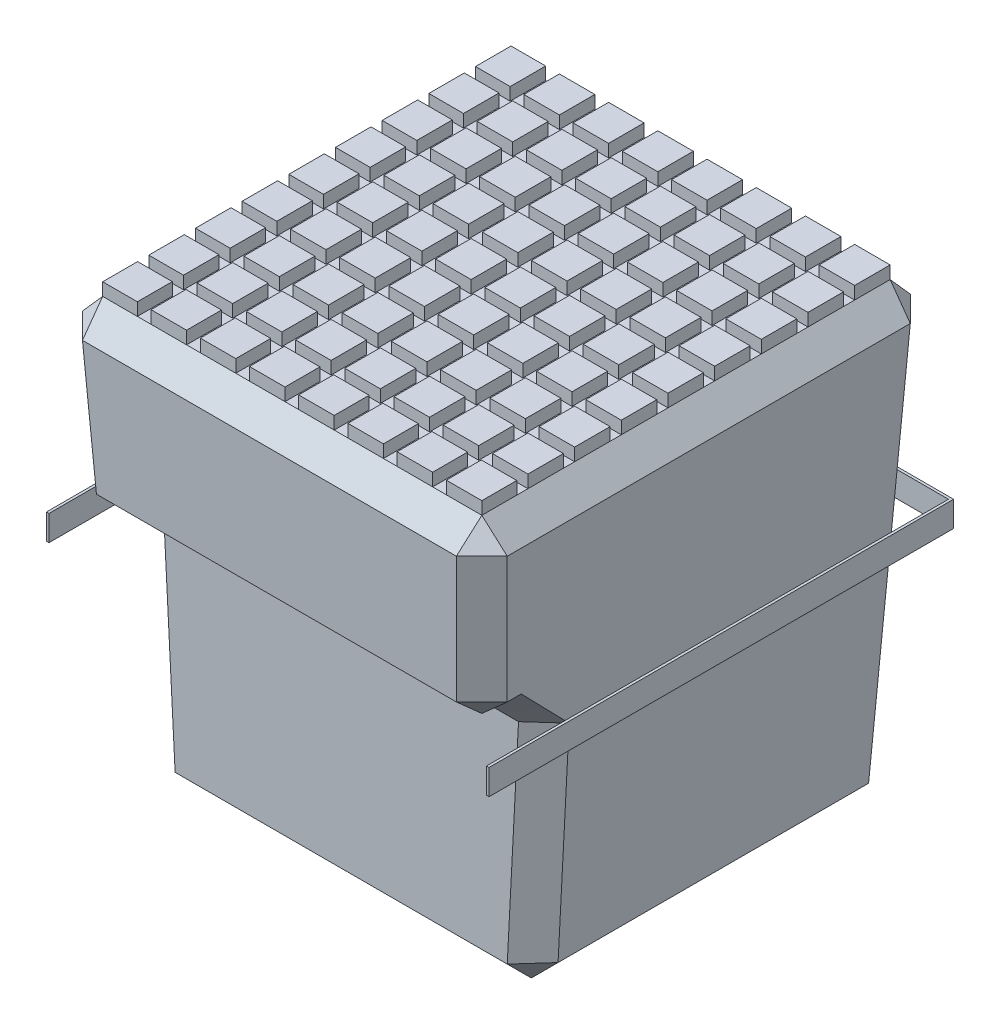
SolidWorks part; units mm, degrees
material "Stainless Steel 2205"
ref_plane "Front Plane" through (0, 0, 0) normal (0, 0, 1) x (1, 0, 0)
ref_plane "Top Plane" through (0, 0, 0) normal (0, 1, 0) x (1, 0, 0)
ref_plane "Right Plane" through (0, 0, 0) normal (1, 0, 0) x (0, 0, -1)
sketch "Sketch2" plane through (0, 0, 0) normal (0, 1, 0) x (1, 0, 0)
  line L1 (168.5, 180) -> (-168.5, 180)
  line L2 (168.5, 180) -> (168.5, -180)
  line L3 (168.5, -180) -> (-168.5, -180)
  line L4 (-168.5, 180) -> (-168.5, -180)
  line L5 (168.5, 180) -> (-168.5, -180) construction
  line L6 (168.5, -180) -> (-168.5, 180) construction
  point P0 (0, 0)
  dimension "D1" = 337
  dimension "D2" = 360
extrude "Boss-Extrude1" add sketch "Sketch2" against normal blind 355 draft 3
sketch "Sketch4" plane through (0, 0, 0) normal (1, 0, 0) x (0, 0, -1)
  line L0 (-172.4009, -145) -> (-122.4009, -145)
  line L1 (-161.3952, -355) -> (-180, 0) construction
  line L2 (-122.4009, -145) -> (-122.4009, -355)
  line L3 (-161.3952, -355) -> (161.3952, -355) construction
  line L4 (-122.4009, -355) -> (-170.6976, -355)
  line L5 (-170.6976, -355) -> (-172.4009, -145)
  dimension "D1" = 50
  dimension "D2" = 210
extrude "Cut-Extrude1" cut sketch "Sketch4" against normal through all and the other way through all
chamfer "Chamfer1" distance 20 angle 45 18 edges at (-159.1976, -177.5, -170.6976) (159.1976, -177.5, -170.6976) (-164.7004, -72.5, 176.2004) (0, 0, -180) (-168.5, 0, 0) (168.5, 0, 0) (0, 0, 180) (164.7004, -72.5, 176.2004) (-160.9009, -145, 147.4009) (160.9009, -145, 147.4009) (0, -145, 172.4009) (149.8952, -355, -19.4972) (0, -355, -161.3952) (-149.8952, -355, -19.4972) (0, -145, 122.4009) (155.3981, -250, 122.4009) (0, -355, 122.4009) (-155.3981, -250, 122.4009)
sketch "Sketch5" plane through (0, 0, 0) normal (0, 1, 0) x (1, 0, 0)
  line L0 (0, 122.6349) -> (0, -123.659)
  line L1 (149.4699, 124.1699) -> (149.4699, 96.1699)
  line L2 (149.4699, 160.9699) -> (121.4699, 160.9699)
  line L3 (149.4699, 160.9699) -> (149.4699, 132.9699)
  line L4 (149.4699, 132.9699) -> (121.4699, 132.9699)
  line L5 (121.4699, 160.9699) -> (121.4699, 132.9699)
  line L6 (149.4699, 124.1699) -> (121.4699, 124.1699)
  line L7 (121.4699, 124.1699) -> (121.4699, 96.1699)
  line L8 (149.4699, 96.1699) -> (121.4699, 96.1699)
  line L9 (149.4699, 87.3699) -> (149.4699, 59.3699)
  line L10 (149.4699, 87.3699) -> (121.4699, 87.3699)
  line L11 (121.4699, 87.3699) -> (121.4699, 59.3699)
  line L12 (149.4699, 59.3699) -> (121.4699, 59.3699)
  line L13 (149.4699, 50.5699) -> (149.4699, 22.5699)
  line L14 (149.4699, 50.5699) -> (121.4699, 50.5699)
  line L15 (121.4699, 50.5699) -> (121.4699, 22.5699)
  line L16 (149.4699, 22.5699) -> (121.4699, 22.5699)
  line L17 (149.4699, 13.7699) -> (149.4699, -14.2301)
  line L18 (149.4699, 13.7699) -> (121.4699, 13.7699)
  line L19 (121.4699, 13.7699) -> (121.4699, -14.2301)
  line L20 (149.4699, -14.2301) -> (121.4699, -14.2301)
  line L21 (149.4699, -23.0301) -> (149.4699, -51.0301)
  line L22 (149.4699, -23.0301) -> (121.4699, -23.0301)
  line L23 (121.4699, -23.0301) -> (121.4699, -51.0301)
  line L24 (149.4699, -51.0301) -> (121.4699, -51.0301)
  line L25 (149.4699, -59.8301) -> (149.4699, -87.8301)
  line L26 (149.4699, -59.8301) -> (121.4699, -59.8301)
  line L27 (121.4699, -59.8301) -> (121.4699, -87.8301)
  line L28 (149.4699, -87.8301) -> (121.4699, -87.8301)
  line L29 (149.4699, -96.6301) -> (149.4699, -124.6301)
  line L30 (149.4699, -96.6301) -> (121.4699, -96.6301)
  line L31 (121.4699, -96.6301) -> (121.4699, -124.6301)
  line L32 (149.4699, -124.6301) -> (121.4699, -124.6301)
  line L33 (149.4699, -133.4301) -> (149.4699, -161.4301)
  line L34 (149.4699, -133.4301) -> (121.4699, -133.4301)
  line L35 (121.4699, -133.4301) -> (121.4699, -161.4301)
  line L36 (149.4699, -161.4301) -> (121.4699, -161.4301)
  line L37 (149.4699, 160.9699) -> (149.4699, 124.1699) construction
  line L38 (110.6699, 160.9699) -> (110.6699, 132.9699)
  line L39 (110.6699, 160.9699) -> (82.6699, 160.9699)
  line L40 (82.6699, 160.9699) -> (82.6699, 132.9699)
  line L41 (110.6699, 132.9699) -> (82.6699, 132.9699)
  line L42 (71.8699, 160.9699) -> (71.8699, 132.9699)
  line L43 (71.8699, 160.9699) -> (43.8699, 160.9699)
  line L44 (43.8699, 160.9699) -> (43.8699, 132.9699)
  line L45 (71.8699, 132.9699) -> (43.8699, 132.9699)
  line L46 (33.0699, 160.9699) -> (33.0699, 132.9699)
  line L47 (33.0699, 160.9699) -> (5.0699, 160.9699)
  line L48 (5.0699, 160.9699) -> (5.0699, 132.9699)
  line L49 (33.0699, 132.9699) -> (5.0699, 132.9699)
  line L50 (-5.7301, 160.9699) -> (-5.7301, 132.9699)
  line L51 (-5.7301, 160.9699) -> (-33.7301, 160.9699)
  line L52 (-33.7301, 160.9699) -> (-33.7301, 132.9699)
  line L53 (-5.7301, 132.9699) -> (-33.7301, 132.9699)
  line L54 (-44.5301, 160.9699) -> (-44.5301, 132.9699)
  line L55 (-44.5301, 160.9699) -> (-72.5301, 160.9699)
  line L56 (-72.5301, 160.9699) -> (-72.5301, 132.9699)
  line L57 (-44.5301, 132.9699) -> (-72.5301, 132.9699)
  line L58 (-83.3301, 160.9699) -> (-83.3301, 132.9699)
  line L59 (-83.3301, 160.9699) -> (-111.3301, 160.9699)
  line L60 (-111.3301, 160.9699) -> (-111.3301, 132.9699)
  line L61 (-83.3301, 132.9699) -> (-111.3301, 132.9699)
  line L62 (-122.1301, 160.9699) -> (-122.1301, 132.9699)
  line L63 (-122.1301, 160.9699) -> (-150.1301, 160.9699)
  line L64 (-150.1301, 160.9699) -> (-150.1301, 132.9699)
  line L65 (-122.1301, 132.9699) -> (-150.1301, 132.9699)
  line L66 (110.6699, 124.1699) -> (110.6699, 96.1699)
  line L67 (110.6699, 124.1699) -> (82.6699, 124.1699)
  line L68 (82.6699, 124.1699) -> (82.6699, 96.1699)
  line L69 (110.6699, 96.1699) -> (82.6699, 96.1699)
  line L70 (71.8699, 124.1699) -> (71.8699, 96.1699)
  line L71 (71.8699, 124.1699) -> (43.8699, 124.1699)
  line L72 (43.8699, 124.1699) -> (43.8699, 96.1699)
  line L73 (71.8699, 96.1699) -> (43.8699, 96.1699)
  line L74 (33.0699, 124.1699) -> (33.0699, 96.1699)
  line L75 (33.0699, 124.1699) -> (5.0699, 124.1699)
  line L76 (5.0699, 124.1699) -> (5.0699, 96.1699)
  line L77 (33.0699, 96.1699) -> (5.0699, 96.1699)
  line L78 (-5.7301, 124.1699) -> (-5.7301, 96.1699)
  line L79 (-5.7301, 124.1699) -> (-33.7301, 124.1699)
  line L80 (-33.7301, 124.1699) -> (-33.7301, 96.1699)
  line L81 (-5.7301, 96.1699) -> (-33.7301, 96.1699)
  line L82 (-44.5301, 124.1699) -> (-44.5301, 96.1699)
  line L83 (-44.5301, 124.1699) -> (-72.5301, 124.1699)
  line L84 (-72.5301, 124.1699) -> (-72.5301, 96.1699)
  line L85 (-44.5301, 96.1699) -> (-72.5301, 96.1699)
  line L86 (-83.3301, 124.1699) -> (-83.3301, 96.1699)
  line L87 (-83.3301, 124.1699) -> (-111.3301, 124.1699)
  line L88 (-111.3301, 124.1699) -> (-111.3301, 96.1699)
  line L89 (-83.3301, 96.1699) -> (-111.3301, 96.1699)
  line L90 (-122.1301, 124.1699) -> (-122.1301, 96.1699)
  line L91 (-122.1301, 124.1699) -> (-150.1301, 124.1699)
  line L92 (-150.1301, 124.1699) -> (-150.1301, 96.1699)
  line L93 (-122.1301, 96.1699) -> (-150.1301, 96.1699)
  line L94 (110.6699, 87.3699) -> (110.6699, 59.3699)
  line L95 (110.6699, 87.3699) -> (82.6699, 87.3699)
  line L96 (82.6699, 87.3699) -> (82.6699, 59.3699)
  line L97 (110.6699, 59.3699) -> (82.6699, 59.3699)
  line L98 (71.8699, 87.3699) -> (71.8699, 59.3699)
  line L99 (71.8699, 87.3699) -> (43.8699, 87.3699)
  line L100 (43.8699, 87.3699) -> (43.8699, 59.3699)
  line L101 (71.8699, 59.3699) -> (43.8699, 59.3699)
  line L102 (33.0699, 87.3699) -> (33.0699, 59.3699)
  line L103 (33.0699, 87.3699) -> (5.0699, 87.3699)
  line L104 (5.0699, 87.3699) -> (5.0699, 59.3699)
  line L105 (33.0699, 59.3699) -> (5.0699, 59.3699)
  line L106 (-5.7301, 87.3699) -> (-5.7301, 59.3699)
  line L107 (-5.7301, 87.3699) -> (-33.7301, 87.3699)
  line L108 (-33.7301, 87.3699) -> (-33.7301, 59.3699)
  line L109 (-5.7301, 59.3699) -> (-33.7301, 59.3699)
  line L110 (-44.5301, 87.3699) -> (-44.5301, 59.3699)
  line L111 (-44.5301, 87.3699) -> (-72.5301, 87.3699)
  line L112 (-72.5301, 87.3699) -> (-72.5301, 59.3699)
  line L113 (-44.5301, 59.3699) -> (-72.5301, 59.3699)
  line L114 (-83.3301, 87.3699) -> (-83.3301, 59.3699)
  line L115 (-83.3301, 87.3699) -> (-111.3301, 87.3699)
  line L116 (-111.3301, 87.3699) -> (-111.3301, 59.3699)
  line L117 (-83.3301, 59.3699) -> (-111.3301, 59.3699)
  line L118 (-122.1301, 87.3699) -> (-122.1301, 59.3699)
  line L119 (-122.1301, 87.3699) -> (-150.1301, 87.3699)
  line L120 (-150.1301, 87.3699) -> (-150.1301, 59.3699)
  line L121 (-122.1301, 59.3699) -> (-150.1301, 59.3699)
  line L122 (110.6699, 50.5699) -> (110.6699, 22.5699)
  line L123 (110.6699, 50.5699) -> (82.6699, 50.5699)
  line L124 (82.6699, 50.5699) -> (82.6699, 22.5699)
  line L125 (110.6699, 22.5699) -> (82.6699, 22.5699)
  line L126 (71.8699, 50.5699) -> (71.8699, 22.5699)
  line L127 (71.8699, 50.5699) -> (43.8699, 50.5699)
  line L128 (43.8699, 50.5699) -> (43.8699, 22.5699)
  line L129 (71.8699, 22.5699) -> (43.8699, 22.5699)
  line L130 (33.0699, 50.5699) -> (33.0699, 22.5699)
  line L131 (33.0699, 50.5699) -> (5.0699, 50.5699)
  line L132 (5.0699, 50.5699) -> (5.0699, 22.5699)
  line L133 (33.0699, 22.5699) -> (5.0699, 22.5699)
  line L134 (-5.7301, 50.5699) -> (-5.7301, 22.5699)
  line L135 (-5.7301, 50.5699) -> (-33.7301, 50.5699)
  line L136 (-33.7301, 50.5699) -> (-33.7301, 22.5699)
  line L137 (-5.7301, 22.5699) -> (-33.7301, 22.5699)
  line L138 (-44.5301, 50.5699) -> (-44.5301, 22.5699)
  line L139 (-44.5301, 50.5699) -> (-72.5301, 50.5699)
  line L140 (-72.5301, 50.5699) -> (-72.5301, 22.5699)
  line L141 (-44.5301, 22.5699) -> (-72.5301, 22.5699)
  line L142 (-83.3301, 50.5699) -> (-83.3301, 22.5699)
  line L143 (-83.3301, 50.5699) -> (-111.3301, 50.5699)
  line L144 (-111.3301, 50.5699) -> (-111.3301, 22.5699)
  line L145 (-83.3301, 22.5699) -> (-111.3301, 22.5699)
  line L146 (-122.1301, 50.5699) -> (-122.1301, 22.5699)
  line L147 (-122.1301, 50.5699) -> (-150.1301, 50.5699)
  line L148 (-150.1301, 50.5699) -> (-150.1301, 22.5699)
  line L149 (-122.1301, 22.5699) -> (-150.1301, 22.5699)
  line L150 (110.6699, 13.7699) -> (110.6699, -14.2301)
  line L151 (110.6699, 13.7699) -> (82.6699, 13.7699)
  line L152 (82.6699, 13.7699) -> (82.6699, -14.2301)
  line L153 (110.6699, -14.2301) -> (82.6699, -14.2301)
  line L154 (71.8699, 13.7699) -> (71.8699, -14.2301)
  line L155 (71.8699, 13.7699) -> (43.8699, 13.7699)
  line L156 (43.8699, 13.7699) -> (43.8699, -14.2301)
  line L157 (71.8699, -14.2301) -> (43.8699, -14.2301)
  line L158 (33.0699, 13.7699) -> (33.0699, -14.2301)
  line L159 (33.0699, 13.7699) -> (5.0699, 13.7699)
  line L160 (5.0699, 13.7699) -> (5.0699, -14.2301)
  line L161 (33.0699, -14.2301) -> (5.0699, -14.2301)
  line L162 (-5.7301, 13.7699) -> (-5.7301, -14.2301)
  line L163 (-5.7301, 13.7699) -> (-33.7301, 13.7699)
  line L164 (-33.7301, 13.7699) -> (-33.7301, -14.2301)
  line L165 (-5.7301, -14.2301) -> (-33.7301, -14.2301)
  line L166 (-44.5301, 13.7699) -> (-44.5301, -14.2301)
  line L167 (-44.5301, 13.7699) -> (-72.5301, 13.7699)
  line L168 (-72.5301, 13.7699) -> (-72.5301, -14.2301)
  line L169 (-44.5301, -14.2301) -> (-72.5301, -14.2301)
  line L170 (-83.3301, 13.7699) -> (-83.3301, -14.2301)
  line L171 (-83.3301, 13.7699) -> (-111.3301, 13.7699)
  line L172 (-111.3301, 13.7699) -> (-111.3301, -14.2301)
  line L173 (-83.3301, -14.2301) -> (-111.3301, -14.2301)
  line L174 (-122.1301, 13.7699) -> (-122.1301, -14.2301)
  line L175 (-122.1301, 13.7699) -> (-150.1301, 13.7699)
  line L176 (-150.1301, 13.7699) -> (-150.1301, -14.2301)
  line L177 (-122.1301, -14.2301) -> (-150.1301, -14.2301)
  line L178 (110.6699, -23.0301) -> (110.6699, -51.0301)
  line L179 (110.6699, -23.0301) -> (82.6699, -23.0301)
  line L180 (82.6699, -23.0301) -> (82.6699, -51.0301)
  line L181 (110.6699, -51.0301) -> (82.6699, -51.0301)
  line L182 (71.8699, -23.0301) -> (71.8699, -51.0301)
  line L183 (71.8699, -23.0301) -> (43.8699, -23.0301)
  line L184 (43.8699, -23.0301) -> (43.8699, -51.0301)
  line L185 (71.8699, -51.0301) -> (43.8699, -51.0301)
  line L186 (33.0699, -23.0301) -> (33.0699, -51.0301)
  line L187 (33.0699, -23.0301) -> (5.0699, -23.0301)
  line L188 (5.0699, -23.0301) -> (5.0699, -51.0301)
  line L189 (33.0699, -51.0301) -> (5.0699, -51.0301)
  line L190 (-5.7301, -23.0301) -> (-5.7301, -51.0301)
  line L191 (-5.7301, -23.0301) -> (-33.7301, -23.0301)
  line L192 (-33.7301, -23.0301) -> (-33.7301, -51.0301)
  line L193 (-5.7301, -51.0301) -> (-33.7301, -51.0301)
  line L194 (-44.5301, -23.0301) -> (-44.5301, -51.0301)
  line L195 (-44.5301, -23.0301) -> (-72.5301, -23.0301)
  line L196 (-72.5301, -23.0301) -> (-72.5301, -51.0301)
  line L197 (-44.5301, -51.0301) -> (-72.5301, -51.0301)
  line L198 (-83.3301, -23.0301) -> (-83.3301, -51.0301)
  line L199 (-83.3301, -23.0301) -> (-111.3301, -23.0301)
  line L200 (-111.3301, -23.0301) -> (-111.3301, -51.0301)
  line L201 (-83.3301, -51.0301) -> (-111.3301, -51.0301)
  line L202 (-122.1301, -23.0301) -> (-122.1301, -51.0301)
  line L203 (-122.1301, -23.0301) -> (-150.1301, -23.0301)
  line L204 (-150.1301, -23.0301) -> (-150.1301, -51.0301)
  line L205 (-122.1301, -51.0301) -> (-150.1301, -51.0301)
  line L206 (110.6699, -59.8301) -> (110.6699, -87.8301)
  line L207 (110.6699, -59.8301) -> (82.6699, -59.8301)
  line L208 (82.6699, -59.8301) -> (82.6699, -87.8301)
  line L209 (110.6699, -87.8301) -> (82.6699, -87.8301)
  line L210 (71.8699, -59.8301) -> (71.8699, -87.8301)
  line L211 (71.8699, -59.8301) -> (43.8699, -59.8301)
  line L212 (43.8699, -59.8301) -> (43.8699, -87.8301)
  line L213 (71.8699, -87.8301) -> (43.8699, -87.8301)
  line L214 (33.0699, -59.8301) -> (33.0699, -87.8301)
  line L215 (33.0699, -59.8301) -> (5.0699, -59.8301)
  line L216 (5.0699, -59.8301) -> (5.0699, -87.8301)
  line L217 (33.0699, -87.8301) -> (5.0699, -87.8301)
  line L218 (-5.7301, -59.8301) -> (-5.7301, -87.8301)
  line L219 (-5.7301, -59.8301) -> (-33.7301, -59.8301)
  line L220 (-33.7301, -59.8301) -> (-33.7301, -87.8301)
  line L221 (-5.7301, -87.8301) -> (-33.7301, -87.8301)
  line L222 (-44.5301, -59.8301) -> (-44.5301, -87.8301)
  line L223 (-44.5301, -59.8301) -> (-72.5301, -59.8301)
  line L224 (-72.5301, -59.8301) -> (-72.5301, -87.8301)
  line L225 (-44.5301, -87.8301) -> (-72.5301, -87.8301)
  line L226 (-83.3301, -59.8301) -> (-83.3301, -87.8301)
  line L227 (-83.3301, -59.8301) -> (-111.3301, -59.8301)
  line L228 (-111.3301, -59.8301) -> (-111.3301, -87.8301)
  line L229 (-83.3301, -87.8301) -> (-111.3301, -87.8301)
  line L230 (-122.1301, -59.8301) -> (-122.1301, -87.8301)
  line L231 (-122.1301, -59.8301) -> (-150.1301, -59.8301)
  line L232 (-150.1301, -59.8301) -> (-150.1301, -87.8301)
  line L233 (-122.1301, -87.8301) -> (-150.1301, -87.8301)
  line L234 (110.6699, -96.6301) -> (110.6699, -124.6301)
  line L235 (110.6699, -96.6301) -> (82.6699, -96.6301)
  line L236 (82.6699, -96.6301) -> (82.6699, -124.6301)
  line L237 (110.6699, -124.6301) -> (82.6699, -124.6301)
  line L238 (71.8699, -96.6301) -> (71.8699, -124.6301)
  line L239 (71.8699, -96.6301) -> (43.8699, -96.6301)
  line L240 (43.8699, -96.6301) -> (43.8699, -124.6301)
  line L241 (71.8699, -124.6301) -> (43.8699, -124.6301)
  line L242 (33.0699, -96.6301) -> (33.0699, -124.6301)
  line L243 (33.0699, -96.6301) -> (5.0699, -96.6301)
  line L244 (5.0699, -96.6301) -> (5.0699, -124.6301)
  line L245 (33.0699, -124.6301) -> (5.0699, -124.6301)
  line L246 (-5.7301, -96.6301) -> (-5.7301, -124.6301)
  line L247 (-5.7301, -96.6301) -> (-33.7301, -96.6301)
  line L248 (-33.7301, -96.6301) -> (-33.7301, -124.6301)
  line L249 (-5.7301, -124.6301) -> (-33.7301, -124.6301)
  line L250 (-44.5301, -96.6301) -> (-44.5301, -124.6301)
  line L251 (-44.5301, -96.6301) -> (-72.5301, -96.6301)
  line L252 (-72.5301, -96.6301) -> (-72.5301, -124.6301)
  line L253 (-44.5301, -124.6301) -> (-72.5301, -124.6301)
  line L254 (-83.3301, -96.6301) -> (-83.3301, -124.6301)
  line L255 (-83.3301, -96.6301) -> (-111.3301, -96.6301)
  line L256 (-111.3301, -96.6301) -> (-111.3301, -124.6301)
  line L257 (-83.3301, -124.6301) -> (-111.3301, -124.6301)
  line L258 (-122.1301, -96.6301) -> (-122.1301, -124.6301)
  line L259 (-122.1301, -96.6301) -> (-150.1301, -96.6301)
  line L260 (-150.1301, -96.6301) -> (-150.1301, -124.6301)
  line L261 (-122.1301, -124.6301) -> (-150.1301, -124.6301)
  line L262 (110.6699, -133.4301) -> (110.6699, -161.4301)
  line L263 (110.6699, -133.4301) -> (82.6699, -133.4301)
  line L264 (82.6699, -133.4301) -> (82.6699, -161.4301)
  line L265 (110.6699, -161.4301) -> (82.6699, -161.4301)
  line L266 (71.8699, -133.4301) -> (71.8699, -161.4301)
  line L267 (71.8699, -133.4301) -> (43.8699, -133.4301)
  line L268 (43.8699, -133.4301) -> (43.8699, -161.4301)
  line L269 (71.8699, -161.4301) -> (43.8699, -161.4301)
  line L270 (33.0699, -133.4301) -> (33.0699, -161.4301)
  line L271 (33.0699, -133.4301) -> (5.0699, -133.4301)
  line L272 (5.0699, -133.4301) -> (5.0699, -161.4301)
  line L273 (33.0699, -161.4301) -> (5.0699, -161.4301)
  line L274 (-5.7301, -133.4301) -> (-5.7301, -161.4301)
  line L275 (-5.7301, -133.4301) -> (-33.7301, -133.4301)
  line L276 (-33.7301, -133.4301) -> (-33.7301, -161.4301)
  line L277 (-5.7301, -161.4301) -> (-33.7301, -161.4301)
  line L278 (-44.5301, -133.4301) -> (-44.5301, -161.4301)
  line L279 (-44.5301, -133.4301) -> (-72.5301, -133.4301)
  line L280 (-72.5301, -133.4301) -> (-72.5301, -161.4301)
  line L281 (-44.5301, -161.4301) -> (-72.5301, -161.4301)
  line L282 (-83.3301, -133.4301) -> (-83.3301, -161.4301)
  line L283 (-83.3301, -133.4301) -> (-111.3301, -133.4301)
  line L284 (-111.3301, -133.4301) -> (-111.3301, -161.4301)
  line L285 (-83.3301, -161.4301) -> (-111.3301, -161.4301)
  line L286 (-122.1301, -133.4301) -> (-122.1301, -161.4301)
  line L287 (-122.1301, -133.4301) -> (-150.1301, -133.4301)
  line L288 (-150.1301, -133.4301) -> (-150.1301, -161.4301)
  line L289 (-122.1301, -161.4301) -> (-150.1301, -161.4301)
  line L290 (149.4699, 124.1699) -> (149.4699, 96.1699)
  line L291 (149.4699, 124.1699) -> (121.4699, 124.1699)
  line L292 (121.4699, 124.1699) -> (121.4699, 96.1699)
  line L293 (149.4699, 96.1699) -> (121.4699, 96.1699)
  line L294 (149.4699, 87.3699) -> (149.4699, 59.3699)
  line L295 (149.4699, 87.3699) -> (121.4699, 87.3699)
  line L296 (121.4699, 87.3699) -> (121.4699, 59.3699)
  line L297 (149.4699, 59.3699) -> (121.4699, 59.3699)
  line L298 (149.4699, 50.5699) -> (149.4699, 22.5699)
  line L299 (149.4699, 50.5699) -> (121.4699, 50.5699)
  line L300 (121.4699, 50.5699) -> (121.4699, 22.5699)
  line L301 (149.4699, 22.5699) -> (121.4699, 22.5699)
  line L302 (149.4699, 13.7699) -> (149.4699, -14.2301)
  line L303 (149.4699, 13.7699) -> (121.4699, 13.7699)
  line L304 (121.4699, 13.7699) -> (121.4699, -14.2301)
  line L305 (149.4699, -14.2301) -> (121.4699, -14.2301)
  line L306 (149.4699, -23.0301) -> (149.4699, -51.0301)
  line L307 (149.4699, -23.0301) -> (121.4699, -23.0301)
  line L308 (121.4699, -23.0301) -> (121.4699, -51.0301)
  line L309 (149.4699, -51.0301) -> (121.4699, -51.0301)
  line L310 (149.4699, -59.8301) -> (149.4699, -87.8301)
  line L311 (149.4699, -59.8301) -> (121.4699, -59.8301)
  line L312 (121.4699, -59.8301) -> (121.4699, -87.8301)
  line L313 (149.4699, -87.8301) -> (121.4699, -87.8301)
  line L314 (149.4699, -96.6301) -> (149.4699, -124.6301)
  line L315 (149.4699, -96.6301) -> (121.4699, -96.6301)
  line L316 (121.4699, -96.6301) -> (121.4699, -124.6301)
  line L317 (149.4699, -124.6301) -> (121.4699, -124.6301)
  line L318 (149.4699, -133.4301) -> (149.4699, -161.4301)
  line L319 (149.4699, -133.4301) -> (121.4699, -133.4301)
  line L320 (121.4699, -133.4301) -> (121.4699, -161.4301)
  line L321 (149.4699, -161.4301) -> (121.4699, -161.4301)
  line M37 (149.4699, -160.9699) -> (149.4699, 160.9699)
  line M38 (149.4699, 160.9699) -> (-149.4699, 160.9699)
  line M39 (-149.4699, 160.9699) -> (-149.4699, -160.9699)
  line M40 (-149.4699, -160.9699) -> (149.4699, -160.9699)
  dimension "D1" = 28
  dimension "D2" = 28
  dimension "D4" = 36.8
  dimension "D3" = 9
  dimension "D5" = 8
  dimension "D6" = 9
extrude "Boss-Extrude2" add sketch "Sketch5" along normal blind 10 contours L65 L62 M38 M39 | L61 L58 L60 M38 | L57 L54 L56 M38 | L49 L46 L48 M38 | L45 L42 L44 M38 | L41 L38 L40 M38 | L5 L4 M38 M37 | L8 L6 L7 M37 | L73 L70 L71 L72 | L77 L74 L75 L76 | L81 L78 L79 L80 | L85 L82 L83 L84 | L89 L86 L87 L88 | L93 L90 L91 M39 | L121 L118 L119 M39 | L117 L114 L115 L116 | L113 L110 L111 L112 | L109 L106 L107 L108 | L105 L102 L103 L104 | L101 L98 L99 L100 | L97 L94 L95 L96 | L125 L122 L123 L124 | L129 L126 L127 L128 | L133 L130 L131 L132 | L137 L134 L135 L136 | L145 L142 L143 L144 | L149 L146 L147 M39 | L141 L138 L139 L140 | L173 L170 L171 L172 | L177 L174 L175 M39 | L205 L202 L203 M39 | L201 L198 L199 L200 | L197 L194 L195 L196 | L193 L190 L191 L192 | L161 L158 L159 L160 | L185 L182 L183 L184 | L157 L154 L155 L156 | L153 L150 L151 L152 | L181 L178 L179 L180 | L24 L22 L23 M37 | L20 L18 L19 M37 | L28 L26 L27 M37 | L237 L234 L235 L236 | L32 L30 L31 M37 | L34 L35 M40 M37 | L263 L264 L262 M40 | L267 L268 L266 M40 | L241 L238 L239 L240 | L217 L214 L215 L216 | L245 L242 L243 L244 | L271 L272 L270 M40 | L275 L276 L274 M40 | L249 L246 L247 L248 | L221 L218 L219 L220 | L225 L222 L223 L224 | L253 L250 L251 L252 | L279 L280 L278 M40 | L213 L210 L211 L212 | L209 L206 L207 L208 | L257 L254 L255 L256 | L229 L226 L227 L228 | L233 L230 L231 M39 | L261 L258 L259 M39 | L286 L287 M39 M40 | L283 L284 L282 M40 | L50 L53 L52 L51 | L69 L68 L67 L66 | L11 L12 L9 L10 | L14 L15 L16 L13 | L167 L168 L169 L166 | L162 L165 L164 L163 | L187 L188 L189 L186
ref_plane "Plane1" through (0, -160, 0) normal (0, 1, 0) x (1, 0, 0)
sketch "Sketch7" plane through (0, -160, 0) normal (0, 1, 0) x (1, 0, 0)
  line L0 (174.4533, 174.7038) -> (174.4533, -15.2426)
  line L2 (172.4533, -15.2426) -> (172.4533, 183.9533)
  line L3 (172.4533, 183.9533) -> (-172.4533, 183.9533)
  line L4 (-172.4533, 183.9533) -> (-172.4533, -15.2426)
  line L6 (-174.4533, -15.2426) -> (-174.4533, 185.9533)
  line L7 (-174.4533, 185.9533) -> (174.4533, 185.9533)
  line L8 (174.4533, 185.9533) -> (174.4533, 174.7038)
  line L9 (-167.4533, -158.8708) -> (-167.4533, 158.9259) construction
  line L10 (167.4533, 158.8708) -> (167.4533, -158.9259) construction
  line L11 (-147.3708, 178.9533) -> (147.4259, 178.9533) construction
  line L12 (174.4533, -15.2426) -> (174.4533, -180.3118)
  line L13 (174.4533, -180.3118) -> (172.4533, -180.3118)
  line L14 (172.4533, -180.3118) -> (172.4533, -15.2426)
  line L15 (-172.4533, -15.2426) -> (-172.4533, -180.3118)
  line L16 (-172.4533, -180.3118) -> (-174.4533, -180.3118)
  line L17 (-174.4533, -180.3118) -> (-174.4533, -15.2426)
  dimension "D1" = 2
  dimension "D2" = 2
  dimension "D3" = 5
  dimension "D4" = 5
  dimension "D5" = 2
  dimension "D6" = 5
  dimension "D7" = 2
extrude "Boss-Extrude3" add sketch "Sketch7" along normal blind 10 and the other way blind 10 separate body
